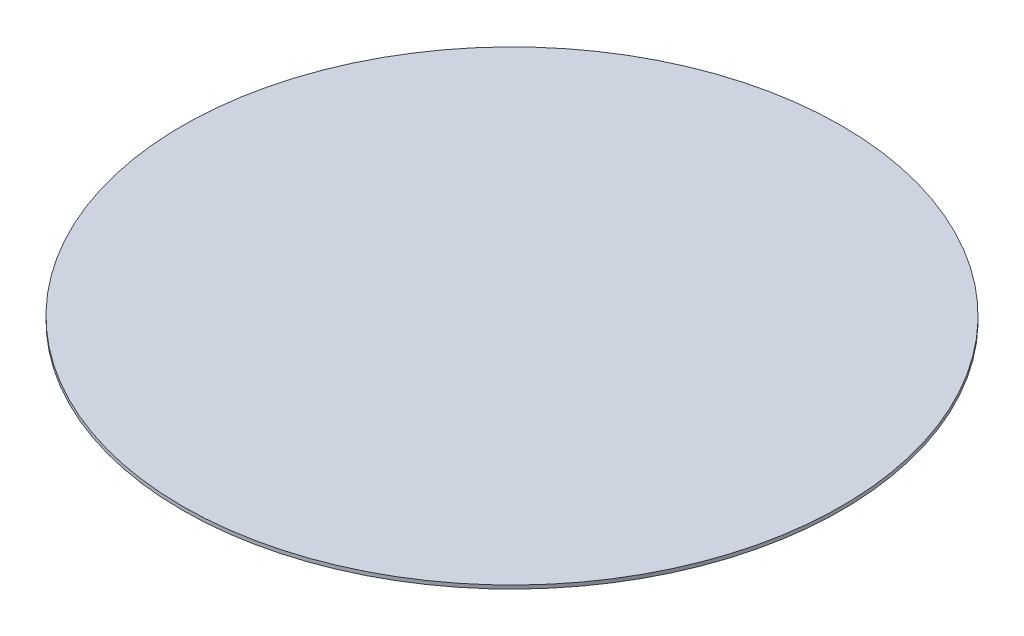
SolidWorks part; units mm, degrees
material "6061 Alloy"
ref_plane "Front Plane" through (0, 0, 0) normal (0, 0, 1) x (1, 0, 0)
ref_plane "Top Plane" through (0, 0, 0) normal (0, 1, 0) x (1, 0, 0)
ref_plane "Right Plane" through (0, 0, 0) normal (1, 0, 0) x (0, 0, -1)
sketch "Sketch1" plane through (0, 0, 0) normal (0, 1, 0) x (1, 0, 0)
  circle A0 centre (0, 0) radius 150
  dimension "D1" = 300
extrude "Boss-Extrude1" add sketch "Sketch1" along normal blind 1.6 contours A0
